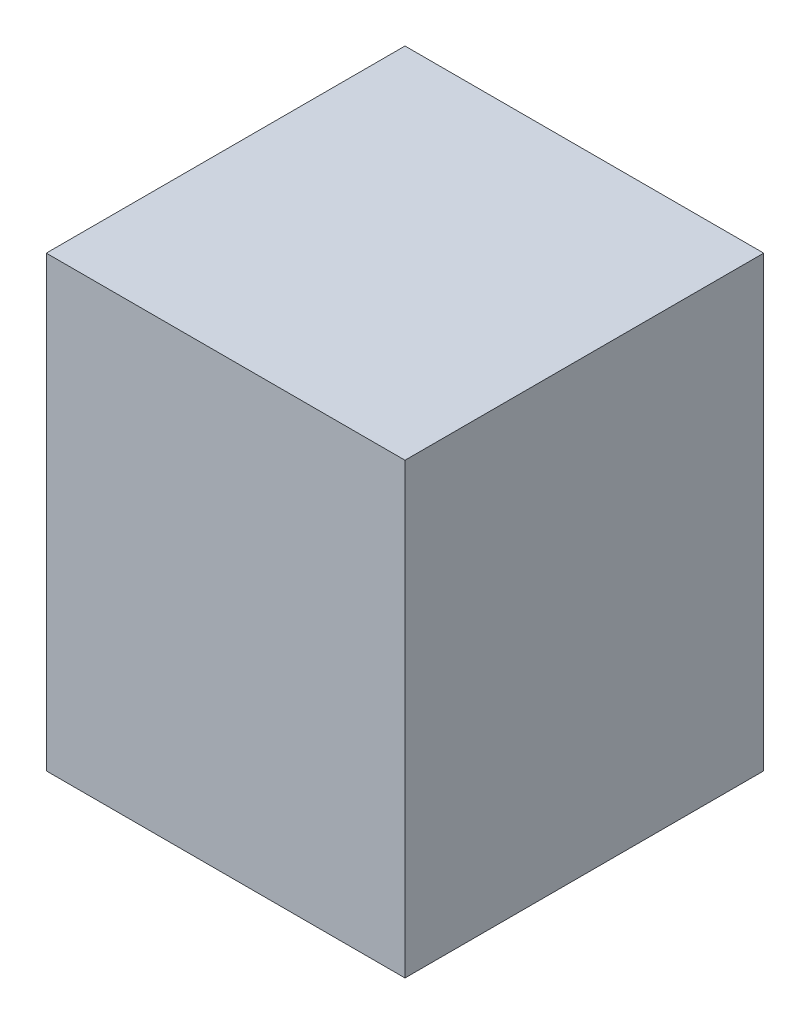
SolidWorks part; units mm, degrees
ref_plane "Спереди" through (0, 0, 0) normal (0, 0, 1) x (1, 0, 0)
ref_plane "Сверху" through (0, 0, 0) normal (0, 1, 0) x (1, 0, 0)
ref_plane "Справа" through (0, 0, 0) normal (1, 0, 0) x (0, 0, -1)
sketch "Эскиз1" plane through (0, 0, 0) normal (0, 0, 1) x (1, 0, 0)
  line L0 (0, 0) -> (4, 0)
  line L1 (4, 0) -> (4, 5)
  line L2 (4, 5) -> (0, 5)
  line L3 (0, 5) -> (0, 0)
  dimension "D1" = 5
  dimension "D2" = 4
extrude "Бобышка-Вытянуть1" add sketch "Эскиз1" along normal blind 4
